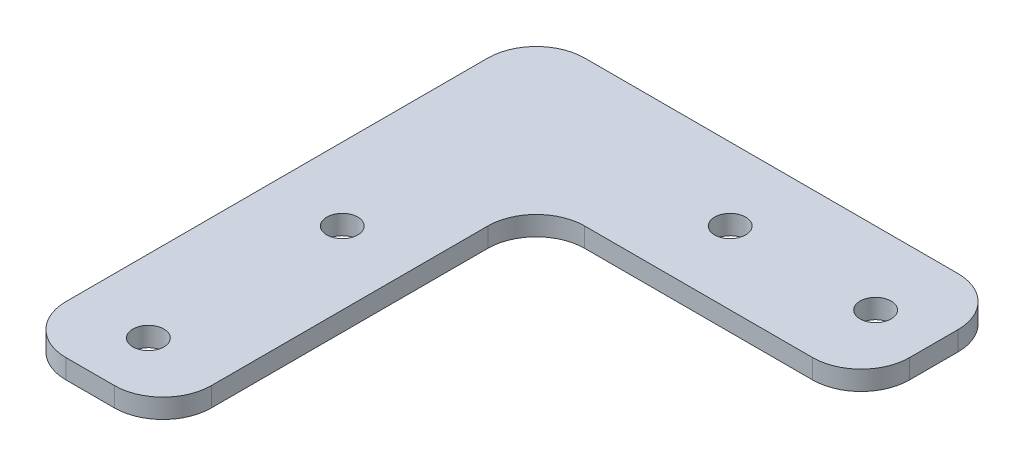
SolidWorks part; units mm, degrees
material "Carbon Fiber"
ref_plane "Front Plane" through (0, 0, 0) normal (0, 0, 1) x (1, 0, 0)
ref_plane "Top Plane" through (0, 0, 0) normal (0, 1, 0) x (1, 0, 0)
ref_plane "Right Plane" through (0, 0, 0) normal (1, 0, 0) x (0, 0, -1)
sketch "Sketch1" plane through (0, 0, 0) normal (0, 1, 0) x (1, 0, 0)
  line L0 (0, -40) -> (0, 0) construction
  line L1 (0, 0) -> (7.5, -7.5) construction
  line L2 (7.5, -7.5) -> (7.5, -46)
  line L3 (7.5, -46) -> (-7.5, -46)
  line L4 (-7.5, -46) -> (-7.5, 7.5)
  line L5 (41, 7.5) -> (-7.5, 7.5)
  line L6 (41, -7.5) -> (41, 7.5)
  line L7 (7.5, -7.5) -> (41, -7.5)
  circle A0 centre (0, -40) radius 1.6
  circle A1 centre (0, -20) radius 1.6
  circle A2 centre (20, 0) radius 1.6
  circle A3 centre (35, 0) radius 1.6
  point P16 (0, -40)
  point P17 (37.8281, -0.5528)
  point P18 (0, -40)
  point P19 (0, 0)
  point P20 (0, 0)
  point P21 (0, 0)
  point P22 (0, 0)
  point P23 (40.8518, -7.5)
  dimension "D2" = 7.5
  dimension "D3" = 20
  dimension "D1" = 3.2
  dimension "D4" = 15
  dimension "D5" = 15
  dimension "D6" = 6
  dimension "D7" = 6
extrude "Boss-Extrude1" add sketch "Sketch1" along normal blind 2
fillet "Fillet1" radius 5 6 edges at (7.5, 1, 46) (-7.5, 1, 46) (-7.5, 1, -7.5) (41, 1, -7.5) (41, 1, 7.5) (7.5, 1, 7.5)
